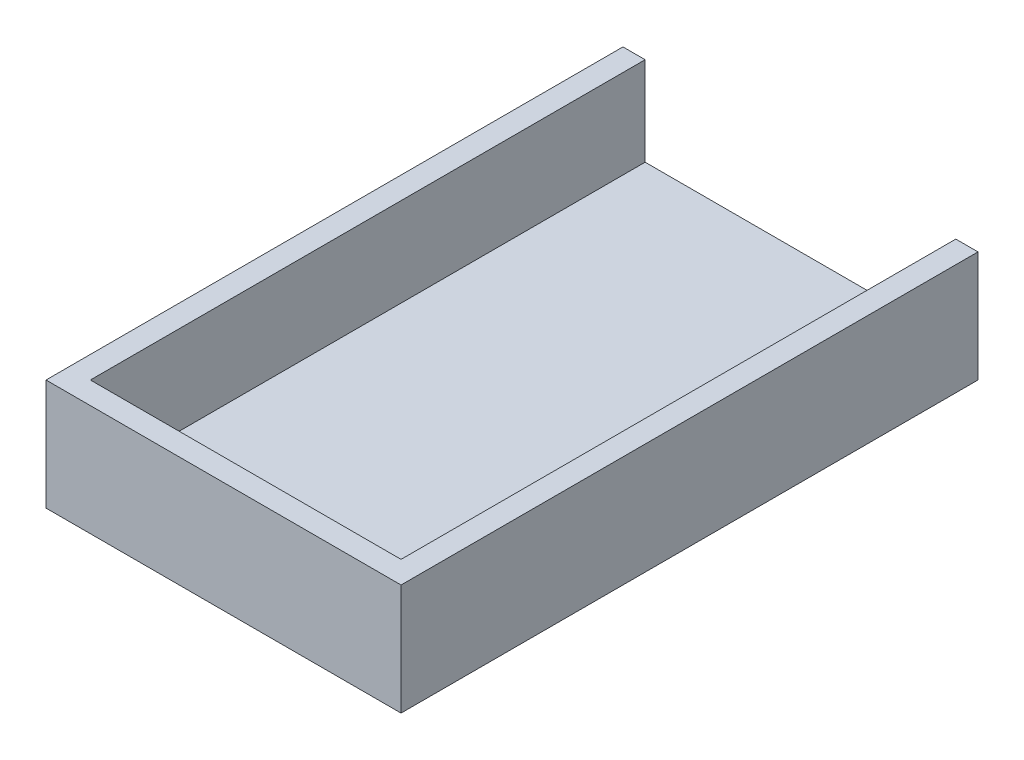
SolidWorks part; units mm, degrees
ref_plane "정면" through (0, 0, 0) normal (0, 0, 1) x (1, 0, 0)
ref_plane "윗면" through (0, 0, 0) normal (0, 1, 0) x (1, 0, 0)
ref_plane "우측면" through (0, 0, 0) normal (1, 0, 0) x (0, 0, -1)
sketch "스케치1" plane through (0, 0, 0) normal (0, 1, 0) x (1, 0, 0)
  line L1 (8, -13) -> (-8, -13)
  line L2 (8, -13) -> (8, 13)
  line L3 (8, 13) -> (-8, 13)
  line L4 (-8, -13) -> (-8, 13)
  line L5 (8, -13) -> (-8, 13) construction
  line L6 (8, 13) -> (-8, -13) construction
  point P0 (0, 0)
  dimension "D1" = 16
  dimension "D2" = 26
extrude "보스-돌출1" add sketch "스케치1" along normal blind 5
sketch "스케치2" plane through (0, 0, 0) normal (0, 1, 0) x (1, 0, 0)
  line L0 (-8, 13) -> (-8, -13) construction
  line L1 (-7, 13) -> (7, 13)
  line L2 (-7, 13) -> (-7, -12)
  line L3 (-7, -12) -> (7, -12)
  line L4 (7, 13) -> (7, -12)
  line L6 (8, 13) -> (-8, 13) construction
  dimension "D1" = 14
  dimension "D2" = 25
  dimension "D3" = 1
extrude "컷-돌출1" cut sketch "스케치2" along normal blind 10 from offset 1
sketch "스케치3" plane through (0, 0, 0) normal (0, 1, 0) x (1, 0, 0)
  line L1 (8, -13) -> (-8, -13)
  line L2 (8, -13) -> (8, 13)
  line L3 (8, 13) -> (-8, 13)
  line L4 (-8, -13) -> (-8, 13)
  line L5 (8, -13) -> (-8, 13) construction
  line L6 (8, 13) -> (-8, -13) construction
  point P0 (0, 0)
extrude "보스-돌출3" add sketch "스케치3" along normal blind 1 from offset 5 separate body
sketch "스케치4" plane through (0, 0, 0) normal (0, 1, 0) x (1, 0, 0)
  line L0 (-8, -13) -> (8, -13) construction
  line L1 (-7, 7) -> (7, 7)
  line L2 (-7, 7) -> (-7, -10)
  line L3 (-7, -10) -> (7, -10)
  line L4 (7, 7) -> (7, -10)
  line L5 (8, -13) -> (8, 13) construction
  dimension "D1" = 3
  dimension "D2" = 17
  dimension "D3" = 14
  dimension "D4" = 1
extrude "컷-돌출2" cut sketch "스케치4" against normal blind 1 from surface at 6 starting at face at (0, 6, 0)
sketch "스케치5" plane through (0, 6, 0) normal (0, 1, 0) x (1, 0, 0)
  line L4 (-8, 13) -> (-8, -13)
  line L5 (-8, -13) -> (8, -13)
  line L6 (8, -13) -> (8, 13)
  line L7 (8, 13) -> (-8, 13)
  line L8 (-8, 13) -> (-8, -13)
  line L9 (-8, -13) -> (8, -13)
  line L10 (8, -13) -> (8, 13)
  line L11 (8, 13) -> (-8, 13)
  dimension "D1" = 0
extrude "컷-돌출3" cut sketch "스케치5" against normal blind 1
